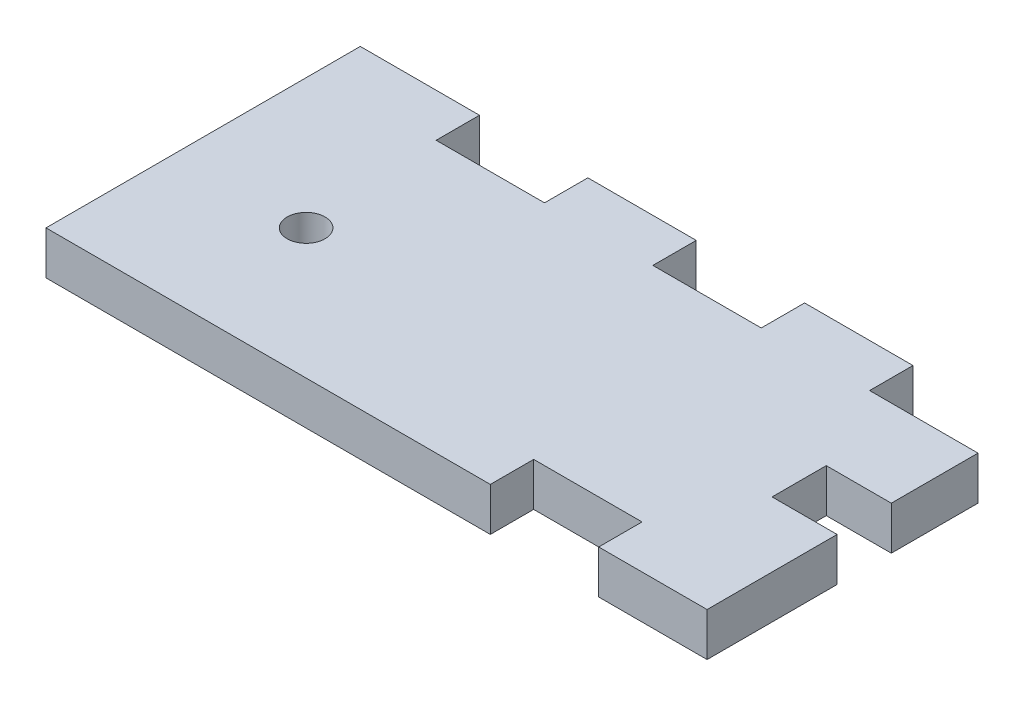
SolidWorks part; units mm, degrees
material "Maple"
ref_plane "Front Plane" through (0, 0, 0) normal (0, 0, 1) x (1, 0, 0)
ref_plane "Top Plane" through (0, 0, 0) normal (0, 1, 0) x (1, 0, 0)
ref_plane "Right Plane" through (0, 0, 0) normal (1, 0, 0) x (0, 0, -1)
sketch "Sketch1" plane through (0, 0, 0) normal (0, 1, 0) x (1, 0, 0)
  line L1 (0, 0) -> (55, 0)
  line L2 (0, 0) -> (0, -21)
  line L3 (0, -21) -> (55, -21)
  line L4 (55, 0) -> (55, -21)
  dimension "D1" = 55
  dimension "D2" = 21
extrude "Boss-Extrude1" add sketch "Sketch1" along normal blind 4
sketch "Sketch2" plane through (55, 0, 0) normal (1, 0, 0) x (0, 0, -1)
  line L0 (-21, 4) -> (0, 4) construction
  line L1 (-21, 4) -> (-13, 4)
  line L2 (-21, 4) -> (-21, 0)
  line L3 (-21, 0) -> (-13, 0)
  line L4 (-13, 4) -> (-13, 0)
  line L5 (-21, 0) -> (0, 0) construction
  line L6 (0, 4) -> (0, 0) construction
  line L7 (0, 4) -> (-8, 4)
  line L8 (0, 4) -> (0, 0)
  line L9 (0, 0) -> (-8, 0)
  line L10 (-8, 4) -> (-8, 0)
  line L11 (-21, 4) -> (-21, 0) construction
  dimension "D1" = 5
extrude "Boss-Extrude2" add sketch "Sketch2" along normal blind 6
sketch "Sketch3" plane through (0, 4, 0) normal (0, 1, 0) x (1, 0, 0)
  line L0 (61, 0) -> (0, 0) construction
  line L1 (51, 0) -> (41, 0)
  line L2 (51, 0) -> (51, 4)
  line L3 (51, 4) -> (41, 4)
  line L4 (41, 0) -> (41, 4)
  line L5 (61, 0) -> (61, -8) construction
  dimension "D1" = 10
  dimension "D2" = 4
  dimension "D3" = 10
extrude "Boss-Extrude3" add sketch "Sketch3" against normal through all
pattern_linear "LPattern1" count 3 spacing 20 along (-1, 0, 0) of "Boss-Extrude3"
sketch "Sketch4" plane through (0, 4, 0) normal (0, 1, 0) x (1, 0, 0)
  line L0 (11, 4) -> (1, 4) construction
  line L1 (1, 4) -> (0, 4)
  line L2 (1, 4) -> (1, 0)
  line L3 (1, 0) -> (0, 0)
  line L4 (0, 4) -> (0, 0)
  point P6 (0, 0)
  point P7 (2.4158, 4)
  point P10 (0.7371, 4)
  point P11 (1, 4)
extrude "Boss-Extrude4" add sketch "Sketch4" against normal through all
sketch "Sketch5" plane through (0, 4, 0) normal (0, 1, 0) x (1, 0, 0)
  line L0 (0, 4) -> (0, -21) construction
  line L1 (0, -21) -> (41, -21)
  line L2 (0, -21) -> (0, -25)
  line L3 (0, -25) -> (41, -25)
  line L4 (41, -21) -> (41, -25)
  line L5 (0, -21) -> (61, -21) construction
  line L6 (61, -13) -> (61, -21) construction
  line L7 (51, -25) -> (61, -25)
  line L8 (51, -25) -> (51, -21)
  line L9 (51, -21) -> (61, -21)
  line L10 (61, -25) -> (61, -21)
  point P12 (0, 0)
  point P15 (41, -23.9173)
  dimension "D1" = 4
  dimension "D3" = 10
  dimension "D4" = 10
extrude "Boss-Extrude5" add sketch "Sketch5" against normal through all
sketch "Sketch6" plane through (0, 4, 0) normal (0, 1, 0) x (1, 0, 0)
  line L0 (0, -25) -> (41, -25) construction
  line L1 (0, 4) -> (0, -25) construction
  circle A0 centre (12, -13) radius 1.75
  dimension "D3" = 3.5
  dimension "D1" = 12
  dimension "D2" = 12
extrude "Cut-Extrude1" cut sketch "Sketch6" against normal through all
